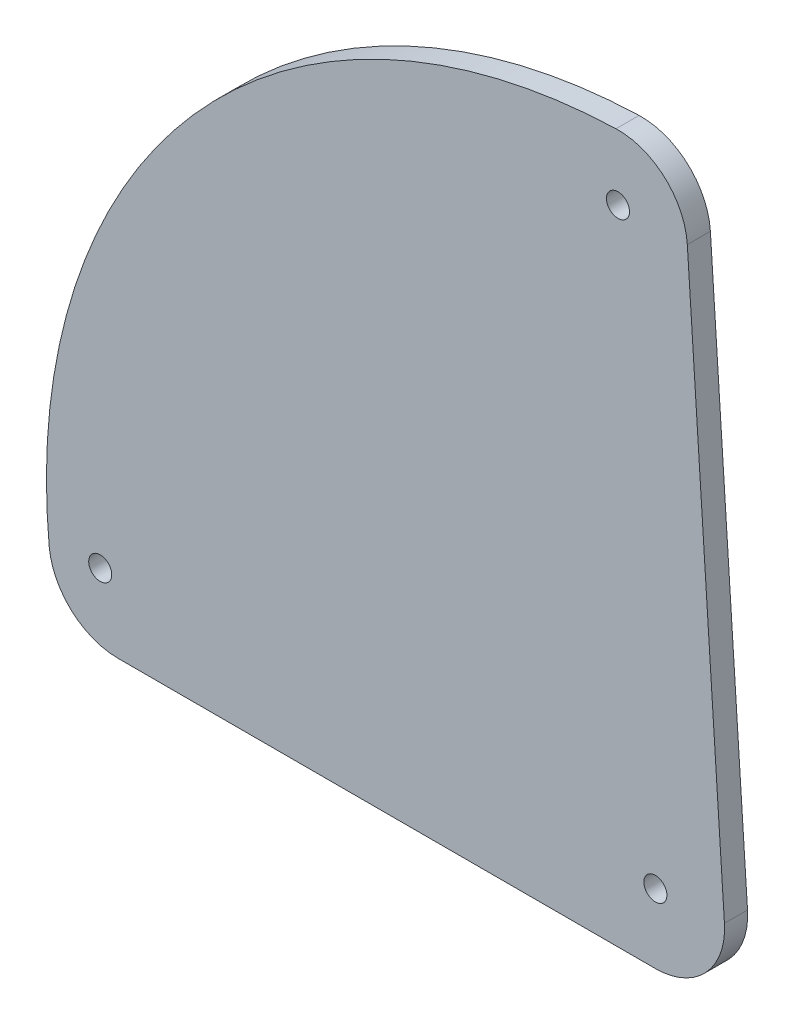
SolidWorks part; units mm, degrees
ref_plane "前视基准面" through (0, 0, 0) normal (0, 0, 1) x (1, 0, 0)
ref_plane "上视基准面" through (0, 0, 0) normal (0, 1, 0) x (1, 0, 0)
ref_plane "右视基准面" through (0, 0, 0) normal (1, 0, 0) x (0, 0, -1)
ref_plane "基准面4" through (0, 0, -18.206) normal (0, 0, 1) x (1, 0, 0)
sketch "草图1" plane through (0, 0, -18.206) normal (0, 0, 1) x (1, 0, 0)
  line L0 (3.8679, -69.618) -> (120.3, -69.618)
  line L1 (135.2682, -53.6418) -> (127.2229, 69.7096)
  circle A0 centre (120.3, -54.618) radius 2.5
  circle A1 centre (112.197, 69.618) radius 2.5
  circle A2 centre (0, -54.618) radius 2.5
  arc A3 (127.2229, 69.7096) -> (111.7717, 83.7256) centre (112.2547, 68.7334) ccw
  arc A4 (111.7717, 83.7256) -> (-11.0619, -56.0672) centre (115.8788, -43.7456) ccw
  arc A5 (-11.0619, -56.0672) -> (3.8679, -69.618) centre (3.8679, -54.618) ccw
  arc A6 (120.3, -69.618) -> (135.2682, -53.6418) centre (120.3, -54.618) ccw
  dimension "D1" = 5
  dimension "D2" = 5
  dimension "D3" = 5
extrude "凸台-拉伸1" add sketch "草图1" against normal blind 5
